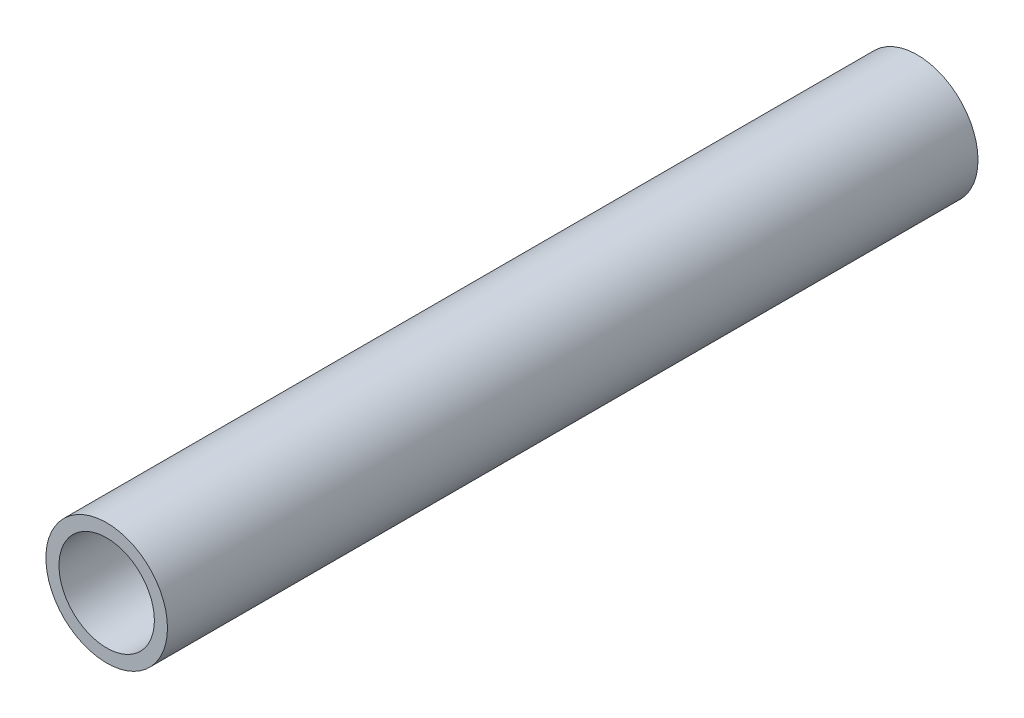
SolidWorks part; units mm, degrees
ref_plane "Front Plane" through (0, 0, 0) normal (0, 0, 1) x (1, 0, 0)
ref_plane "Top Plane" through (0, 0, 0) normal (0, 1, 0) x (1, 0, 0)
ref_plane "Right Plane" through (0, 0, 0) normal (1, 0, 0) x (0, 0, -1)
sketch "Sketch1" plane through (0, 0, 0) normal (0, 0, 1) x (1, 0, 0)
  circle A0 centre (0, 0) radius 10.4648
  circle A1 centre (0, 0) radius 13.335
  dimension "D1" = 2.8702
  dimension "D2" = 26.67
extrude "Boss-Extrude1" add sketch "Sketch1" along normal blind 177.8
